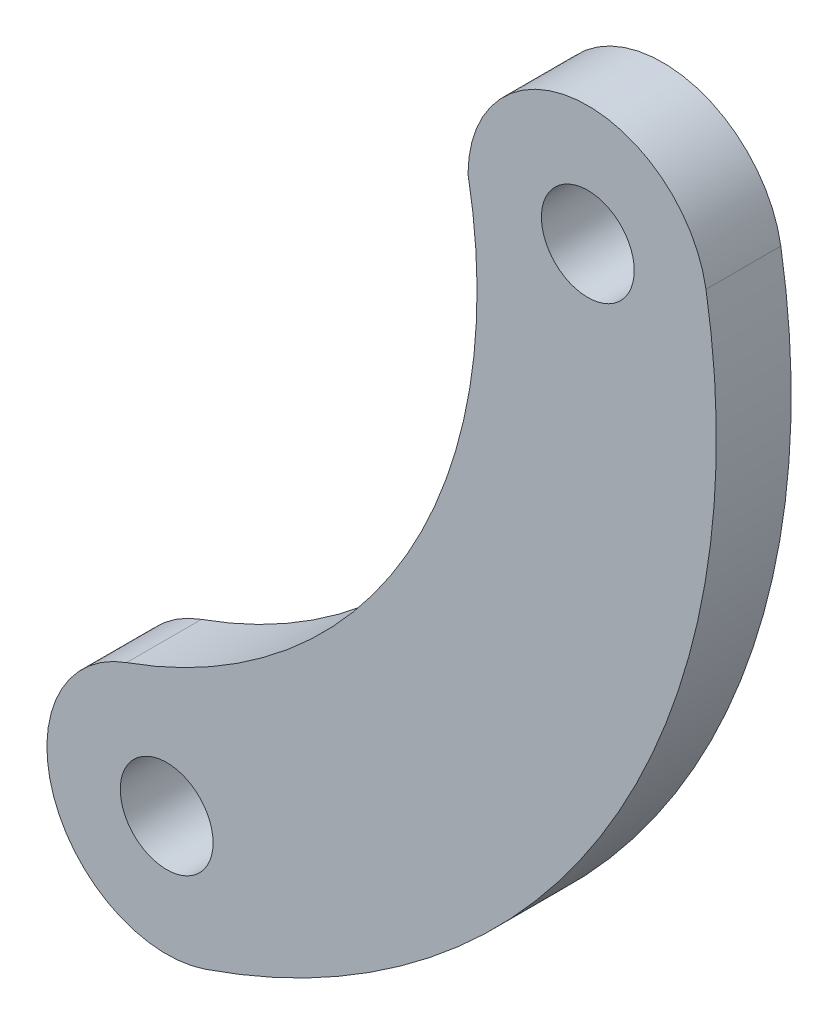
SolidWorks part; units mm, degrees
ref_plane "前视基准面" through (0, 0, 0) normal (0, 0, 1) x (1, 0, 0)
ref_plane "上视基准面" through (0, 0, 0) normal (0, 1, 0) x (1, 0, 0)
ref_plane "右视基准面" through (0, 0, 0) normal (1, 0, 0) x (0, 0, -1)
sketch "草图1" plane through (0, 0, 0) normal (0, 0, 1) x (1, 0, 0)
  arc A0 (3.7882, -5.1312) -> (-7.6166, -24.9713) centre (-13.5144, -8.383) cw
  arc A2 (3.7882, -5.1312) -> (11.7373, -4.4952) centre (7.7902, -5.1561) cw
  arc A3 (11.7373, -4.4952) -> (-4.9834, -32.5256) centre (-13.1363, -8.6599) cw
  arc A4 (-7.6166, -24.9713) -> (-4.9834, -32.5256) centre (-6.2765, -28.7403) ccw
  circle A5 centre (7.7902, -5.1561) radius 1.55
  circle A6 centre (-6.2765, -28.7403) radius 1.55
extrude "凸台-拉伸1" add sketch "草图1" along normal blind 2.5
